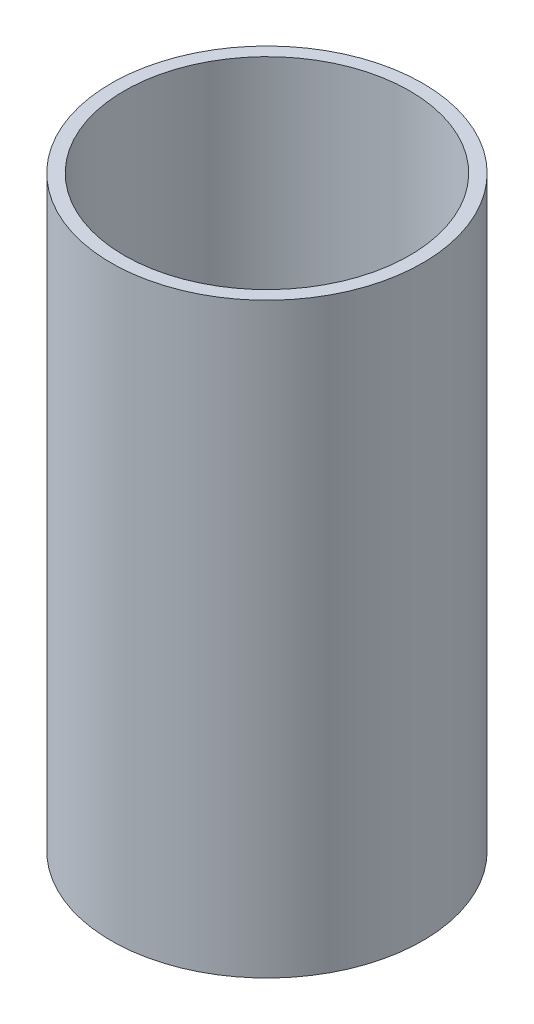
SolidWorks part; units mm, degrees
material "A-Glass Fiber"
ref_plane "Front" through (0, 0, 0) normal (0, 0, 1) x (1, 0, 0)
ref_plane "Top" through (0, 0, 0) normal (0, 1, 0) x (1, 0, 0)
ref_plane "Right" through (0, 0, 0) normal (1, 0, 0) x (0, 0, -1)
sketch "Sketch2" plane through (0, 0, 0) normal (0, 1, 0) x (1, 0, 0)
  circle A0 centre (0, 0) radius 23.875
  circle A1 centre (0, 0) radius 21.875
  dimension "D1" = 47.75
  dimension "D2" = 2
extrude "Boss-Extrude2" add sketch "Sketch2" along normal blind 90
